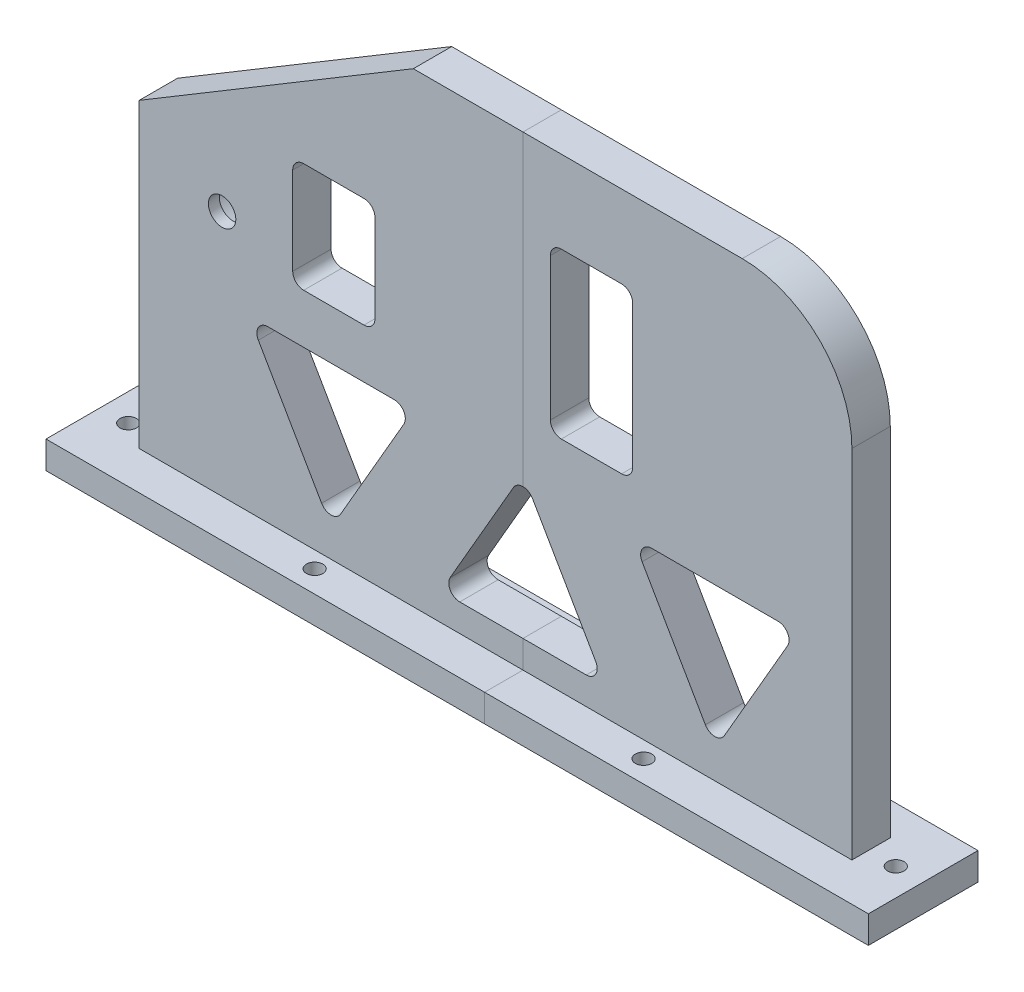
SolidWorks part; units mm, degrees
ref_plane "前视基准面" through (0, 0, 0) normal (0, 0, 1) x (1, 0, 0)
ref_plane "上视基准面" through (0, 0, 0) normal (0, 1, 0) x (1, 0, 0)
ref_plane "右视基准面" through (0, 0, 0) normal (1, 0, 0) x (0, 0, -1)
other "Configuration Table"
sketch "草图3" plane through (0, 0, 0) normal (0, 0, 1) x (1, 0, 0)
  line L0 (0, 0) -> (130, 0)
  line L2 (130, 90) -> (0, 90)
  line L4 (0, 0) -> (0, 90)
  line L5 (130, 90) -> (130, 0)
  dimension "D1" = 90
  dimension "D2" = 130
extrude "凸台-拉伸2" add sketch "草图3" along normal blind 7
hole_wizard "Ø14.0 (14) 直径孔1" positions "草图19" profile "草图20" hole size "Ø5.0" standard "GB" end condition through all
sketch "草图19" plane through (0, 0, 0) normal (0, 0, -1) x (-1, 0, 0)
  point P6 (-15.1208, 50)
sketch "草图20" plane through (15.1208, 50, 0) normal (1, 0, 0) x (0, 1, 0)
  line L0 (0, 0) -> (0, 7)
  line L1 (0, 7) -> (2.5, 7)
  line L2 (2.5, 7) -> (2.5, 0)
  line L5 (2.5, 0) -> (0, 0)
  line L11 (0, -6.35) -> (0, 107.95) construction
  dimension "通孔孔直径" = 5
  dimension "通孔孔深度" = 7
sketch "草图22" plane through (0, 0, 7) normal (0, 0, 1) x (1, 0, 0)
  circle A0 centre (15.1208, 50) radius 7
  circle A1 centre (55.913, 60) radius 7
  circle A2 centre (107.4518, 70) radius 7
  dimension "D1" = 14
  dimension "D2" = 14
  dimension "D3" = 14
extrude "切除-拉伸4" cut sketch "草图22" against normal blind 5 from offset 2 offset against normal yes
chamfer "倒角2" distance 50 distance2 30 1 edges at (0, 90, 3.5)
fillet "圆角3" radius 20 1 edges at (130, 90, 3.5)
sketch "草图25" plane through (0, 0, 0) normal (0, -1, 0) x (1, 0, 0)
  line L0 (-10, 14) -> (-10, -6)
  line L1 (-10, -6) -> (140, -6)
  line L2 (140, -6) -> (140, 14)
  line L3 (140, 14) -> (-10, 14)
  line L5 (0, 7) -> (130, 7) construction
  line L6 (0, 7) -> (0, 0) construction
  dimension "D1" = 20
  dimension "D2" = 7
  dimension "D3" = 150
  dimension "D4" = 10
extrude "凸台-拉伸3" add sketch "草图25" against normal blind 5
sketch "草图26" plane through (0, 5, 0) normal (0, 1, 0) x (1, 0, 0)
  line L0 (140, -14) -> (-10, -14) construction
  line L1 (0, -7) -> (0, 0) construction
  line L2 (140, 6) -> (140, -14) construction
  line L3 (0, 0) -> (130, 0) construction
  line L4 (0, -7) -> (130, -7) construction
  line L5 (50, -7) -> (0, -7) construction
  line L7 (-10, -14) -> (-10, 6) construction
  circle A0 centre (-5, -4) radius 1.5
  circle A1 centre (135, -4) radius 1.5
  circle A2 centre (35, 3) radius 1.5
  circle A3 centre (95, 3) radius 1.5
  circle A4 centre (35, -10) radius 1.5
  circle A5 centre (95, -10) radius 1.5
  dimension "D1" = 3
  dimension "D2" = 5
  dimension "D3" = 10
  dimension "D4" = 5
  dimension "D5" = 10
  dimension "D6" = 3
  dimension "D7" = 3
  dimension "D8" = 3
  dimension "D9" = 3
  dimension "D10" = 60
  dimension "D11" = 45
  dimension "D12" = 60
extrude "切除-拉伸5" cut sketch "草图26" against normal through all
sketch "草图27" plane through (0, 0, 7) normal (0, 0, 1) x (1, 0, 0)
  line L0 (55, 10) -> (85, 10)
  line L1 (85, 10) -> (70, 35.9808)
  line L2 (70, 35.9808) -> (55, 10)
  line L3 (20, 35.9808) -> (50, 35.9808)
  line L4 (50, 35.9808) -> (35, 10)
  line L5 (35, 10) -> (20, 35.9808)
  line L6 (90, 35.9808) -> (120, 35.9808)
  line L7 (120, 35.9808) -> (105, 10)
  line L8 (105, 10) -> (90, 35.9808)
  line L9 (0, 60) -> (0, 5) construction
  line L10 (0, 5) -> (130, 5) construction
  dimension "D1" = 30
  dimension "D2" = 20
  dimension "D3" = 20
  dimension "D4" = 20
  dimension "D5" = 5
extrude "切除-拉伸6" cut sketch "草图27" against normal up to next
fillet "圆角4" radius 2 9 edges at (70, 35.9808, 3.5) (85, 10, 3.5) (55, 10, 3.5) (105, 10, 3.5) (120, 35.9808, 3.5) (90, 35.9808, 3.5) (20, 35.9808, 3.5) (50, 35.9808, 3.5) (35, 10, 3.5)
sketch "草图28" plane through (0, 0, 0) normal (0, 0, -1) x (-1, 0, 0)
  line L0 (-130, 5) -> (-130, 70) construction
  line L1 (-90, 75) -> (-75, 75)
  line L2 (-90, 75) -> (-90, 45)
  line L3 (-90, 45) -> (-75, 45)
  line L4 (-75, 75) -> (-75, 45)
  line L5 (-43, 65) -> (-28, 65)
  line L6 (-43, 65) -> (-43, 45)
  line L7 (-43, 45) -> (-28, 45)
  line L8 (-28, 65) -> (-28, 45)
  line L9 (-110, 90) -> (-50, 90) construction
  line L10 (0, 60) -> (0, 5) construction
  dimension "D1" = 15
  dimension "D2" = 30
  dimension "D3" = 40
  dimension "D4" = 15
  dimension "D5" = 15
  dimension "D6" = 20
  dimension "D7" = 25
  dimension "D8" = 28
extrude "切除-拉伸7" cut sketch "草图28" against normal through all
fillet "圆角5" radius 2 8 edges at (43, 65, 3.5) (28, 65, 3.5) (28, 45, 3.5) (43, 45, 3.5) (90, 45, 3.5) (75, 45, 3.5) (75, 75, 3.5) (90, 75, 3.5)
ref_plane "基准面1" through (70, 0, 0) normal (-1, 0, 0) x (0, 0, 1)
split "分割1" trim tools "基准面1" bodies to split 121 resulting bodies 122 123
